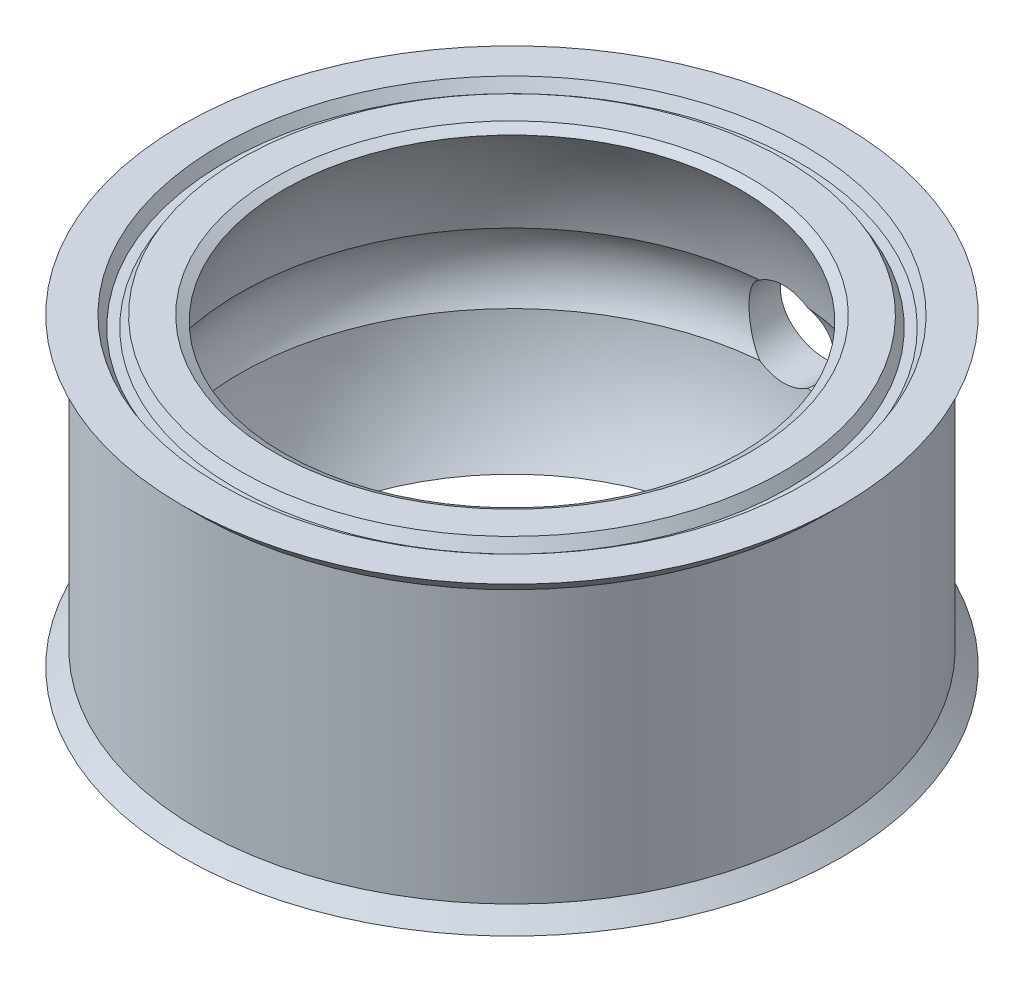
SolidWorks part; units mm, degrees
material "Alloy Steel"
ref_plane "Front Plane" through (0, 0, 0) normal (0, 0, 1) x (1, 0, 0)
ref_plane "Top Plane" through (0, 0, 0) normal (0, 1, 0) x (1, 0, 0)
ref_plane "Right Plane" through (0, 0, 0) normal (1, 0, 0) x (0, 0, -1)
ref_plane "Plane1" through (0, 0, 39.6748) normal (0, 0, 1) x (1, 0, 0)
sketch "Sketch1" plane through (0, 0, 39.6748) normal (0, 0, 1) x (1, 0, 0)
  line L0 (5.3466, -3.4398) -> (5.5698, -3.5687)
  line L1 (5.5698, -3.5687) -> (7.7216, -3.5687)
  line L2 (7.7216, -3.5687) -> (7.3406, -3.1877)
  line L3 (7.3406, -3.1877) -> (7.3406, 3.1877)
  line L4 (7.3406, 3.1877) -> (7.7216, 3.5687)
  line L5 (7.7216, 3.5687) -> (5.5698, 3.5687)
  line L6 (5.5698, 3.5687) -> (5.3466, 3.4398)
  line L7 (0, 3.5687) -> (0, -3.5687) construction
  arc A0 (5.3466, 3.4398) -> (6.3882, 0.817) centre (0.508, 0) cw
  arc A1 (6.3882, -0.817) -> (5.3466, -3.4398) centre (0.508, 0) cw
  spline S0 degree 3 poles (6.3882, 0.817) (6.4796, 0.6663) (6.5463, 0.4978) (6.5827, 0.3253) (6.6191, 0.1528) (6.6263, -0.0283) (6.6036, -0.2031) (6.5808, -0.3778) (6.5276, -0.5511) (6.4483, -0.7085) (6.4297, -0.7454) (6.4096, -0.7817) (6.3882, -0.817) knots 0 0 0 0 0.000529 0.000529 0.000529 0.001058 0.001058 0.001058 0.001586 0.001586 0.001586 0.001709 0.001709 0.001709 0.001709
revolve "Revolve1" add sketch "Sketch1" angle 360 about L7
hole_wizard "M1.6 Clearance Hole1" positions "3DSketch1" profile "Sketch2" hole size "M1.6" standard "ANSI Metric"
sketch3d "3DSketch1"
  point P0 (0, 0, 32.3342)
sketch "Sketch2" plane through (0, 0, 32.3342) normal (1, 0, 0) x (0, 1, 0)
  line L0 (0, 0) -> (0, 0.724)
  line L1 (0, 0.724) -> (0.9906, 0.724)
  line L2 (0.9906, 0.724) -> (0.9906, 0)
  line L5 (0.9906, 0) -> (0, 0)
  line L11 (0, -6.35) -> (0, 107.95) construction
  dimension "Thru Hole Dia." = 1.9812
  dimension "Thru Hole Depth" = 0.724
sketch "Sketch3" plane through (0, 0, 0) normal (1, 0, 0) x (0, 0, -1)
  line L0 (-39.6748, 3.5687) -> (-39.6748, -3.5687) construction
  line L1 (-31.9532, 3.5687) -> (-47.3964, 3.5687) construction
  line L2 (-47.3964, -3.5687) -> (-31.9532, -3.5687) construction
  line L3 (-39.6748, 3.5687) -> (-46.5328, 3.5687) construction
  line L4 (-46.5328, 3.5687) -> (-46.3862, 3.3147)
  line L5 (-46.3862, 3.3147) -> (-46.1714, 3.3147)
  line L6 (-46.1714, 3.3147) -> (-46.0248, 3.5687)
  line L7 (-46.0248, 3.5687) -> (-46.5328, 3.5687)
  line L8 (-46.2788, 3.3147) -> (-46.2788, 3.5687) construction
  dimension "D1" = 0.254
  dimension "D2" = 0.508
  dimension "D3" = 60
  dimension "D4" = 6.35
revolve "Cut-Revolve1" cut sketch "Sketch3" angle 360 about L0
mirror "Mirror1" about plane through (0, 0, 0) normal (0, 1, 0) of "Cut-Revolve1"
sketch "Sketch4" plane through (0, 0, 0) normal (0, 1, 0) x (1, 0, 0)
  point P0 (0, -39.6748)
